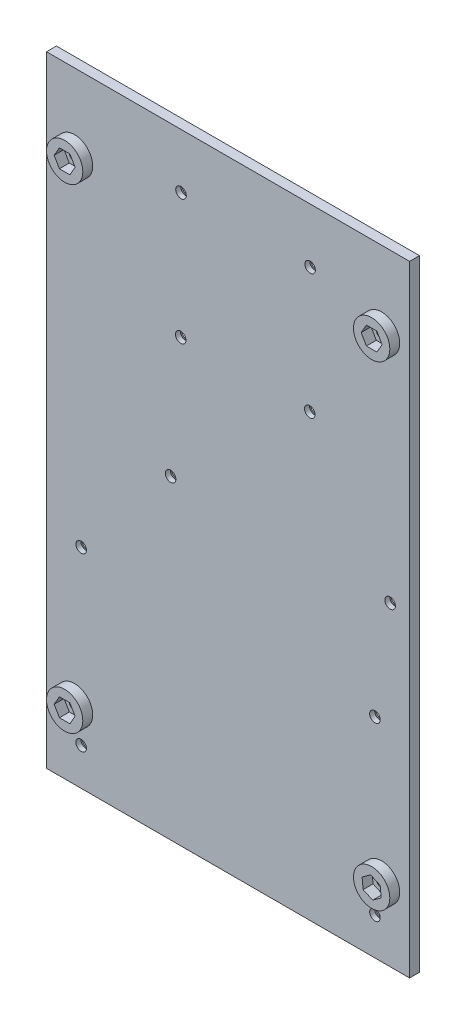
SolidWorks part; units mm, degrees
ref_plane "前视基准面" through (0, 0, 0) normal (0, 0, 1) x (1, 0, 0)
ref_plane "上视基准面" through (0, 0, 0) normal (0, 1, 0) x (1, 0, 0)
ref_plane "右视基准面" through (0, 0, 0) normal (1, 0, 0) x (0, 0, -1)
other "Configuration Table"
sketch "草图1" plane through (0, 0, 0) normal (0, 0, 1) x (1, 0, 0)
  line L1 (-55, 94) -> (55, 94)
  line L2 (-55, 94) -> (-55, -94)
  line L3 (-55, -94) -> (55, -94)
  line L4 (55, 94) -> (55, -94)
  line L5 (-55, 94) -> (55, -94) construction
  line L6 (-55, -94) -> (55, 94) construction
  point P0 (0, 0)
  dimension "D1" = 110
  dimension "D2" = 188
extrude "凸台-拉伸1" add sketch "草图1" along normal blind 3
sketch "草图2" plane through (0, 0, 3) normal (0, 0, 1) x (1, 0, 0)
  line L0 (0, 94) -> (0, -94) construction
  line L1 (-46.5, 71) -> (46.5, 71) construction
  line L2 (-46.5, 71) -> (-46.5, -73) construction
  line L3 (-46.5, -73) -> (46.5, -73) construction
  line L4 (46.5, 71) -> (46.5, -73) construction
  line L5 (-46.5, 71) -> (46.5, -73) construction
  line L6 (-46.5, -73) -> (46.5, 71) construction
  line L7 (55, 94) -> (-55, 94) construction
  line L8 (-55, -94) -> (55, -94) construction
  circle A0 centre (-46.5, 71) radius 1.6
  circle A1 centre (46.5, 71) radius 1.6
  circle A2 centre (-46.5, -73) radius 1.6
  circle A3 centre (46.5, -73) radius 1.6
  point P0 (0, -1)
  point P10 (0, -4.9568)
  dimension "D3" = 23
  dimension "D1" = 93
  dimension "D2" = 144
extrude "切除-拉伸1" cut sketch "草图2" against normal through all
sketch "草图3" plane through (0, 0, 3) normal (0, 0, 1) x (1, 0, 0)
  line L0 (0, 0) -> (0, -94) construction
  line L1 (-44.5, -30.7121) -> (44.5, -30.7121) construction
  line L2 (-44.5, -30.7121) -> (-44.5, -82.7121) construction
  line L3 (-44.5, -82.7121) -> (44.5, -82.7121) construction
  line L4 (44.5, -30.7121) -> (44.5, -82.7121) construction
  line L5 (-44.5, -30.7121) -> (44.5, -82.7121) construction
  line L6 (-44.5, -82.7121) -> (44.5, -30.7121) construction
  line L7 (-55, -94) -> (55, -94) construction
  line L8 (-26.1465, 91.4309) -> (36.3535, 91.4309) construction
  line L9 (-48.5, -26.7121) -> (48.5, -26.7121) construction
  line L10 (-48.5, -26.7121) -> (-48.5, -86.7121) construction
  line L11 (-48.5, -86.7121) -> (48.5, -86.7121) construction
  line L12 (48.5, -26.7121) -> (48.5, -86.7121) construction
  line L13 (-48.5, -26.7121) -> (48.5, -86.7121) construction
  line L14 (-48.5, -86.7121) -> (48.5, -26.7121) construction
  line L15 (-139.0679, 186.3169) -> (-111.0679, 186.3169) construction
  line L16 (-139.0679, 186.3169) -> (-139.0679, 108.3169) construction
  line L17 (-139.0679, 108.3169) -> (-111.0679, 108.3169) construction
  line L18 (-111.0679, 186.3169) -> (-111.0679, 108.3169) construction
  line L19 (-139.0679, 186.3169) -> (-111.0679, 108.3169) construction
  line L20 (-139.0679, 108.3169) -> (-111.0679, 186.3169) construction
  line L21 (-26.1465, 15.4309) -> (51.8535, 15.4309) construction
  line L22 (-26.1465, 15.4309) -> (-26.1465, -12.5691) construction
  line L23 (-26.1465, -12.5691) -> (51.8535, -12.5691) construction
  line L24 (51.8535, 15.4309) -> (51.8535, -12.5691) construction
  line L25 (-26.1465, 15.4309) -> (51.8535, -12.5691) construction
  line L26 (-26.1465, -12.5691) -> (51.8535, 15.4309) construction
  line L27 (-26.1465, 53.4309) -> (36.3535, 53.4309) construction
  line L28 (-26.1465, 53.4309) -> (-26.1465, 25.4309) construction
  line L29 (-26.1465, 25.4309) -> (36.3535, 25.4309) construction
  line L30 (36.3535, 53.4309) -> (36.3535, 25.4309) construction
  line L31 (-26.1465, 53.4309) -> (36.3535, 25.4309) construction
  line L32 (-26.1465, 25.4309) -> (36.3535, 53.4309) construction
  line L33 (-26.1465, 91.4309) -> (-26.1465, 63.4309) construction
  line L34 (-26.1465, 63.4309) -> (36.3535, 63.4309) construction
  line L35 (36.3535, 91.4309) -> (36.3535, 63.4309) construction
  line L36 (-26.1465, 91.4309) -> (36.3535, 63.4309) construction
  line L37 (-26.1465, 63.4309) -> (36.3535, 91.4309) construction
  line L39 (-26.1465, 77.4309) -> (36.3535, 77.4309) construction
  line L40 (-26.1465, 39.4309) -> (36.3535, 39.4309) construction
  line L41 (-26.1465, 1.4309) -> (51.8535, 1.4309) construction
  circle A0 centre (-44.5, -30.7121) radius 1.6
  circle A1 centre (44.5, -30.7121) radius 1.6
  circle A2 centre (44.5, -82.7121) radius 1.6
  circle A3 centre (-44.5, -82.7121) radius 1.6
  circle A4 centre (24.8535, 77.4309) radius 1.6
  circle A5 centre (-14.2465, 77.4309) radius 1.6
  circle A6 centre (24.7615, 39.4309) radius 1.6
  circle A7 centre (-14.3385, 39.4309) radius 1.6
  circle A8 centre (49.1035, 1.4309) radius 1.6
  circle A9 centre (-17.3965, 1.4309) radius 1.6
  point P0 (0, -56.7121)
  point P14 (0, -56.7121)
  point P20 (-125.0679, 147.3169)
  point P26 (5.1035, 39.4309)
  point P28 (12.8535, 1.4309)
  point P40 (5.1035, 77.4309)
  point P57 (0, -55.9711)
  point P58 (2.745, 78.8693)
  point P59 (0, -55.0685)
  point P60 (12.8535, 1.4309)
  point P61 (0, -56.7121)
  dimension "D3" = 97
  dimension "D15" = 11.5
  dimension "D16" = 39.1
  dimension "D17" = 2.75
  dimension "D1" = 89
  dimension "D2" = 52
  dimension "D4" = 60
  dimension "D5" = 28
  dimension "D6" = 78
  dimension "D7" = 78
  dimension "D8" = 28
  dimension "D9" = 28
  dimension "D10" = 62.5
  dimension "D11" = 28
  dimension "D12" = 62.5
  dimension "D13" = 10
  dimension "D14" = 10
  dimension "D18" = 66.5
extrude "切除-拉伸2" cut sketch "草图3" against normal through all
fillet "圆角1" radius 1.5 10 edges at (46.1, -82.7121, 0) (-42.9, -82.7121, 0) (-42.9, -30.7121, 0) (46.1, -30.7121, 0) (50.7035, 1.4309, 0) (-15.7965, 1.4309, 0) (-12.7385, 39.4309, 0) (26.3615, 39.4309, 0) (26.4535, 77.4309, 0) (-12.6465, 77.4309, 0) profile chamfer
sketch "草图4" plane through (0, 0, 3) normal (0, 0, 1) x (1, 0, 0)
  circle A0 centre (-46.5, 71) radius 5.5
  circle A1 centre (46.5, 71) radius 5.5
  circle A2 centre (-46.5, -73) radius 5.5
  circle A3 centre (46.5, -73) radius 5.5
  point P12 (-44.5, -82.7121)
  point P13 (-46.5, -73)
  point P15 (0, 0)
  point P16 (46.5, -73)
extrude "凸台-拉伸2" add sketch "草图4" along normal blind 3
sketch "草图5" plane through (0, 0, 6) normal (0, 0, 1) x (1, 0, 0)
  line L1 (-43.3246, 71) -> (-44.9123, 73.75)
  line L2 (-44.9123, 73.75) -> (-48.0877, 73.75)
  line L3 (-48.0877, 73.75) -> (-49.6754, 71)
  line L4 (-49.6754, 71) -> (-48.0877, 68.25)
  line L5 (-48.0877, 68.25) -> (-44.9123, 68.25)
  line L6 (-44.9123, 68.25) -> (-43.3246, 71)
  line L7 (49.6754, 71) -> (48.0877, 73.75)
  line L8 (48.0877, 73.75) -> (44.9123, 73.75)
  line L9 (44.9123, 73.75) -> (43.3246, 71)
  line L10 (43.3246, 71) -> (44.9123, 68.25)
  line L11 (44.9123, 68.25) -> (48.0877, 68.25)
  line L12 (48.0877, 68.25) -> (49.6754, 71)
  line L13 (-44.8985, -75.742) -> (-43.3246, -72.984)
  line L14 (-43.3246, -72.984) -> (-44.9261, -70.242)
  line L15 (-44.9261, -70.242) -> (-48.1015, -70.258)
  line L16 (-48.1015, -70.258) -> (-49.6754, -73.016)
  line L17 (-49.6754, -73.016) -> (-48.0739, -75.758)
  line L18 (-48.0739, -75.758) -> (-44.8985, -75.742)
  line L19 (46.814, -76.1599) -> (49.3935, -74.308)
  line L20 (49.3935, -74.308) -> (49.0795, -71.1481)
  line L21 (49.0795, -71.1481) -> (46.186, -69.8401)
  line L22 (46.186, -69.8401) -> (43.6065, -71.692)
  line L23 (43.6065, -71.692) -> (43.9205, -74.8519)
  line L24 (43.9205, -74.8519) -> (46.814, -76.1599)
  circle A0 centre (-46.5, 71) radius 2.75 construction
  circle A1 centre (46.5, 71) radius 2.75 construction
  circle A2 centre (-46.5, -73) radius 2.75 construction
  circle A3 centre (46.5, -73) radius 2.75 construction
  dimension "D1" = 5.5
  dimension "D2" = 5.5
  dimension "D3" = 5.5
  dimension "D4" = 5.5
extrude "切除-拉伸3" cut sketch "草图5" against normal blind 3
